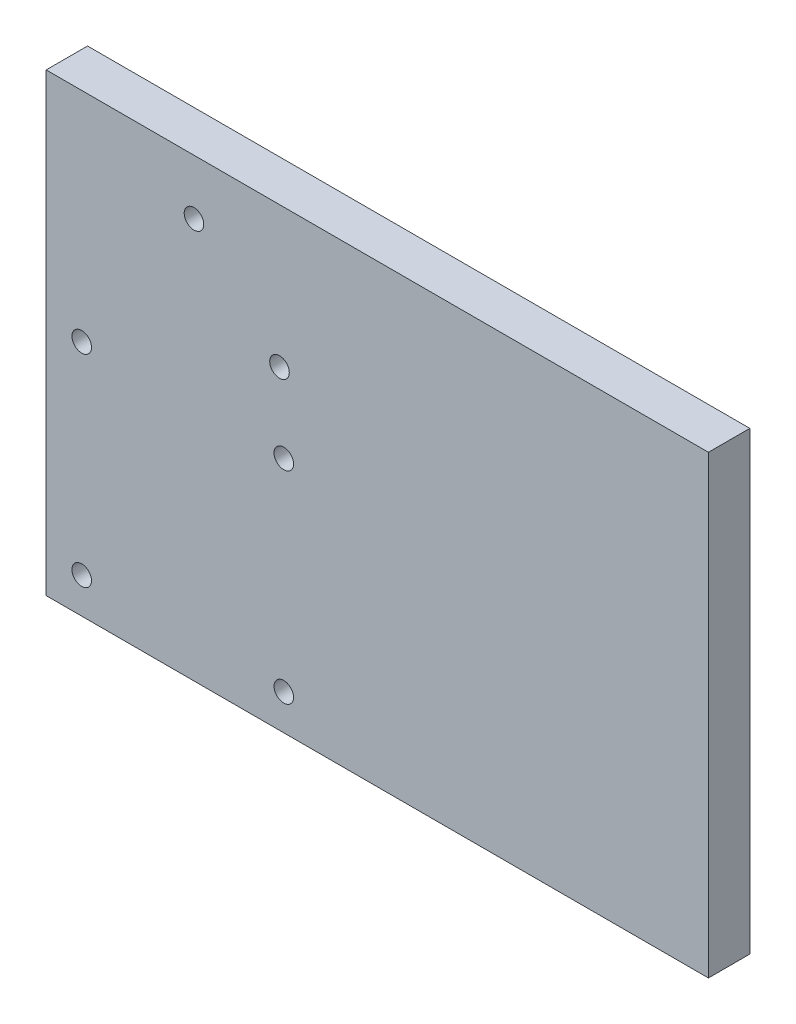
SolidWorks part; units mm, degrees
ref_plane "Front Plane" through (0, 0, 0) normal (0, 0, 1) x (1, 0, 0)
ref_plane "Top Plane" through (0, 0, 0) normal (0, 1, 0) x (1, 0, 0)
ref_plane "Right Plane" through (0, 0, 0) normal (1, 0, 0) x (0, 0, -1)
sketch "Sketch1" plane through (0, 0, 0) normal (0, 0, 1) x (1, 0, 0)
  line L1 (0, 0) -> (101.6, 0)
  line L2 (0, 0) -> (0, 69.85)
  line L3 (0, 69.85) -> (101.6, 69.85)
  line L4 (101.6, 0) -> (101.6, 69.85)
  dimension "D1" = 101.6
  dimension "D2" = 69.85
extrude "Boss-Extrude1" add sketch "Sketch1" along normal blind 6.35
sketch "Sketch2" plane through (0, 0, 6.35) normal (0, 0, 1) x (1, 0, 0)
  circle A0 centre (5.455, 5.455) radius 1.5
  circle A1 centre (5.455, 5.455) radius 1.1303 construction
  circle A2 centre (5.455, 36.455) radius 1.5
  circle A3 centre (36.455, 5.455) radius 1.5
  circle A4 centre (36.455, 36.455) radius 1.5
  circle A5 centre (22.6747, 61.3993) radius 1.5
  circle A6 centre (35.7961, 48.2779) radius 1.5
  circle A7 centre (5.455, 36.455) radius 1.1303 construction
  circle A8 centre (36.455, 36.455) radius 1.1303 construction
  circle A9 centre (36.455, 5.455) radius 1.1303 construction
  circle A10 centre (35.7961, 48.2779) radius 2.25 construction
  circle A11 centre (22.6747, 61.3993) radius 2.25 construction
  dimension "D1" = 3
extrude "Cut-Extrude1" cut sketch "Sketch2" against normal through all
